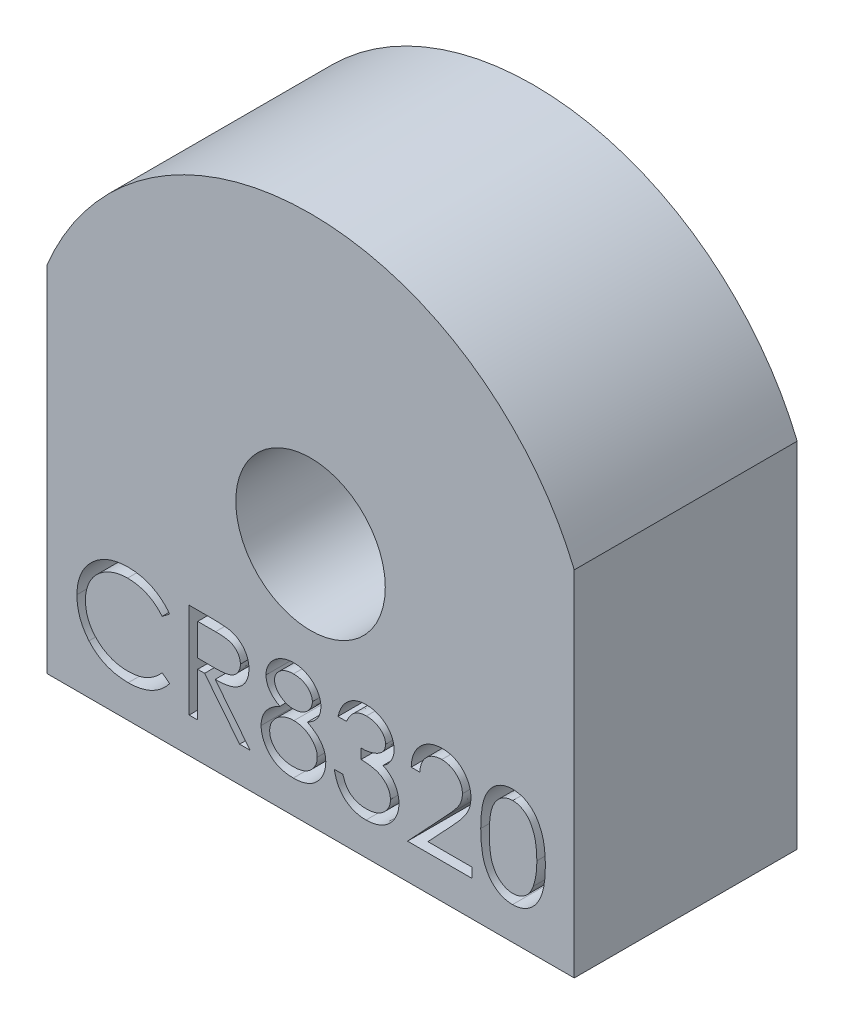
SolidWorks part; units mm, degrees
ref_plane "Front Plane" through (0, 0, 0) normal (0, 0, 1) x (1, 0, 0)
ref_plane "Top Plane" through (0, 0, 0) normal (0, 1, 0) x (1, 0, 0)
ref_plane "Right Plane" through (0, 0, 0) normal (1, 0, 0) x (0, 0, -1)
sketch "Sketch1" plane through (0, 0, 0) normal (0, 0, 1) x (1, 0, 0)
  line L0 (-1000, 0) -> (49000, 0) construction
  line L1 (0, -1000) -> (0, 49000) construction
  line L2 (-1000, 19.5) -> (49000, 19.5) construction
  line L3 (9.7, 13) -> (9.7, 0)
  line L4 (-9.7, 13) -> (-9.7, 0)
  line L5 (-1014.8152, 6.5) -> (48985.1848, 6.5) construction
  line L6 (-1014.0779, 13) -> (48985.9221, 13) construction
  line L7 (-9.7, 0) -> (9.7, 0)
  arc A0 (-9.7, 13) -> (9.7, 13) centre (0, 9.0123) cw
  circle A1 centre (0, 9.0123) radius 2.75
  point P11 (0, 0)
  point P15 (-9.7, 13)
  point P17 (9.7, 13)
  dimension "D6" = 5.5
  dimension "D1" = 19.5
  dimension "D2" = 9.7
  dimension "D3" = 9.7
  dimension "D4" = 6.5
  dimension "D5" = 13
extrude "Boss-Extrude2" add sketch "Sketch1" along normal blind 8.2 contours A0 L3 L7 L4
sketch "Sketch3" plane through (0, 0, 8.2) normal (0, 0, 1) x (1, 0, 0)
  circle A0 centre (0, 8.9682) radius 2.75
  dimension "D1" = 5.5
extrude "Cut-Extrude1" cut sketch "Sketch3" against normal through all
sketch "Sketch4" plane through (0, 0, 8.2) normal (0, 0, 1) x (1, 0, 0)
  text T0 "CR8320"
extrude "Cut-Extrude2" cut sketch "Sketch4" against normal blind 3
equation "\"C\"= 19.5mm"
equation "\"B\"= 19.4mm"
equation "\"D3@Sketch1\"=\"B\"/2"
equation "\"D2@Sketch1\"=\"B\"/2"
equation "\"D1@Sketch1\"=\"C\""
equation "\"D4@Sketch1\"=\"C\"/3"
equation "\"D5@Sketch1\"=\"C\"/3*2"
equation "\"D\"= 8.2mm"
equation "\"D1@Boss-Extrude2\"=\"D\""
